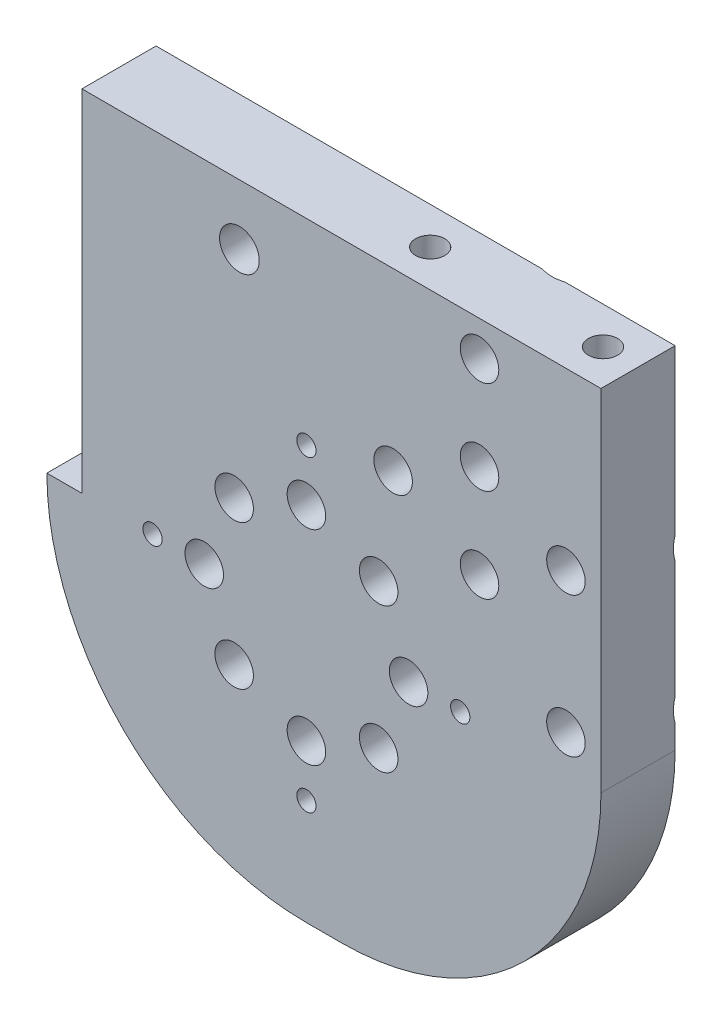
SolidWorks part; units mm, degrees
ref_plane "Front Plane" through (0, 0, 0) normal (0, 0, 1) x (1, 0, 0)
ref_plane "Top Plane" through (0, 0, 0) normal (0, 1, 0) x (1, 0, 0)
ref_plane "Right Plane" through (0, 0, 0) normal (1, 0, 0) x (0, 0, -1)
ref_plane "Plane1" through (0, 0, 0) normal (0, 0, -1) x (-1, 0, 0)
sketch "Sketch1" plane through (0, 0, 0) normal (0, 0, -1) x (-1, 0, 0)
  line L0 (44.45, 0) -> (44.45, 60)
  line L1 (44.45, 60) -> (-44.45, 60)
  line L2 (-44.45, 60) -> (-44.45, 0)
  arc A0 (-44.45, 0) -> (44.45, 0) centre (0, 0) ccw
extrude "Boss-Extrude1" add sketch "Sketch1" against normal blind 12.7
hole_wizard "#4 Clearance Hole1" positions "Sketch3" profile "Sketch2" hole size "#4" standard "ANSI Inch"
sketch "Sketch3" plane through (0, 0, 12.7) normal (0, 0, 1) x (1, 0, 0)
  line L0 (6, 0) -> (6, 26.35) construction
  line L1 (6, 0) -> (32.35, 0) construction
  line L2 (6, 0) -> (6, -26.35) construction
  line L3 (6, 0) -> (-20.35, 0) construction
  circle A0 centre (6, 0) radius 26.35 construction
  point P0 (32.35, 0.009)
  point P1 (6, -26.35)
  point P2 (-20.35, -0.01)
  point P3 (6, 26.35)
  dimension "D1" = 52.7
  dimension "D2" = 6
sketch "Sketch2" plane through (32.35, 0.009, 12.7) normal (1, 0, 0) x (0, -1, 0)
  line L0 (0, 0) -> (0, 12.7)
  line L1 (0, 12.7) -> (1.65, 12.7)
  line L2 (1.65, 12.7) -> (1.65, 0)
  line L5 (1.65, 0) -> (0, 0)
  line L11 (0, -6.35) -> (0, 107.95) construction
  dimension "Thru Hole Dia." = 3.3
  dimension "Thru Hole Depth" = 12.7
hole_wizard "1/4 Clearance Hole1" positions "Sketch5" profile "Sketch4" hole size "1/4" standard "ANSI Inch"
sketch "Sketch5" plane through (0, 0, 0) normal (0, 0, -1) x (-1, 0, 0)
  point P0 (8.85, 30)
  point P1 (23.65, 38)
  point P2 (23.65, 22)
sketch "Sketch4" plane through (-8.85, 30, 0) normal (1, 0, 0) x (0, 1, 0)
  line L0 (0, 0) -> (0, 12.7)
  line L1 (0, 12.7) -> (3.3, 12.7)
  line L2 (3.3, 12.7) -> (3.3, 0)
  line L5 (3.3, 0) -> (0, 0)
  line L11 (0, -6.35) -> (0, 107.95) construction
  dimension "Thru Hole Dia." = 6.6
  dimension "Thru Hole Depth" = 12.7
hole_wizard "1/4 Clearance Hole2" positions "Sketch7" profile "Sketch6" hole size "1/4" standard "ANSI Inch"
sketch "Sketch7" plane through (0, 0, 12.7) normal (0, 0, 1) x (1, 0, 0)
  line L0 (0, 0) -> (0, 60) construction
  line L1 (-44.45, 60) -> (44.45, 60) construction
  point P0 (17.4725, 49.6929)
  dimension "D1" = 17.4725
sketch "Sketch6" plane through (17.4725, 49.6929, 12.7) normal (1, 0, 0) x (0, -1, 0)
  line L0 (0, 0) -> (0, 12.7)
  line L1 (0, 12.7) -> (3.4, 12.7)
  line L2 (3.4, 12.7) -> (3.4, 0)
  line L5 (3.4, 0) -> (0, 0)
  line L11 (0, -6.35) -> (0, 107.95) construction
  dimension "Thru Hole Dia." = 6.8
  dimension "Thru Hole Depth" = 12.7
hole_wizard "CSK for 1/4 Flat Head Machine Screw (100)1" positions "Sketch9" profile "Sketch8" countersink size "1/4" standard "ANSI Inch"
sketch "Sketch9" plane through (0, 0, 0) normal (0, 0, -1) x (-1, 0, 0)
  point P0 (23.65, 54)
  point P1 (38.45, 6)
  point P2 (38.45, 30)
sketch "Sketch8" plane through (-23.65, 54, 0) normal (1, 0, 0) x (0, 1, 0)
  line L0 (0, 0) -> (0, 12.7)
  line L1 (0, 12.7) -> (3.3, 12.7)
  line L2 (3.3, 12.7) -> (3.3, 3)
  line L3 (3.3, 3) -> (6.3, 0)
  line L5 (6.3, 0) -> (0, 0)
  line L6 (-3.3, 3) -> (-6.3, 0) construction
  line L11 (0, -6.35) -> (0, 107.95) construction
  dimension "Thru Hole Dia." = 6.6
  dimension "Thru Hole Depth" = 12.7
  dimension "Near C'Sink Dia." = 12.6
  dimension "Near C'Sink Angle" = 90
hole_wizard "#10 Clearance Hole1" positions "Sketch11" profile "Sketch10" hole size "#10" standard "ANSI Inch"
sketch "Sketch11" plane through (0, 60, 0) normal (0, 1, 0) x (1, 0, 0)
  point P0 (-38.45, -6.35)
  point P1 (-8.85, -6.35)
sketch "Sketch10" plane through (-38.45, 60, 6.35) normal (1, 0, 0) x (0, 0, 1)
  line L0 (0, 0) -> (0, 15)
  line L1 (0, 15) -> (2.5, 15)
  line L2 (2.5, 15) -> (2.5, 0)
  line L5 (2.5, 0) -> (0, 0)
  line L10 (0, 15) -> (-2.5, 15) construction
  line L11 (0, -6.35) -> (0, 107.95) construction
  dimension "Hole Dia." = 5
  dimension "Hole Depth" = 15
  dimension "Drill Angle" = 180
hole_wizard "#10 Clearance Hole2" positions "Sketch13" profile "Sketch12" hole size "#10" standard "ANSI Inch"
sketch "Sketch13" plane through (44.45, 0, 0) normal (1, 0, 0) x (0, 0, -1)
  point P0 (-6.35, 7)
  point P1 (-6.35, 53)
  point P2 (-6.35, 30)
sketch "Sketch12" plane through (44.45, 7, 6.35) normal (0, 1, 0) x (0, 0, -1)
  line L0 (0, 0) -> (0, 10)
  line L1 (0, 10) -> (2.5, 10)
  line L2 (2.5, 10) -> (2.5, 0)
  line L5 (2.5, 0) -> (0, 0)
  line L10 (0, 10) -> (-2.5, 10) construction
  line L11 (0, -6.35) -> (0, 107.95) construction
  dimension "Hole Dia." = 5
  dimension "Hole Depth" = 10
  dimension "Drill Angle" = 180
hole_wizard "1-3/4 Clearance Hole1" positions "Sketch15" profile "Sketch14" hole size "1-3/4" standard "ANSI Inch"
sketch "Sketch15" plane through (0, 0, 0) normal (0, 0, -1) x (-1, 0, 0)
  point P0 (-6, 0)
  dimension "D1" = 6
sketch "Sketch14" plane through (6, 0, 0) normal (1, 0, 0) x (0, 1, 0)
  line L0 (0, 0) -> (0, 5)
  line L1 (0, 5) -> (22.5, 5)
  line L2 (22.5, 5) -> (22.5, 0)
  line L5 (22.5, 0) -> (0, 0)
  line L10 (0, 5) -> (-22.5, 5) construction
  line L11 (0, -6.35) -> (0, 107.95) construction
  dimension "Hole Dia." = 45
  dimension "Hole Depth" = 5
  dimension "Drill Angle" = 180
hole_wizard "1/4 Clearance Hole3" positions "Sketch17" profile "Sketch16" hole size "1/4" standard "ANSI Inch"
sketch "Sketch17" plane through (0, 0, 12.7) normal (0, 0, 1) x (1, 0, 0)
  line L0 (6, 0) -> (6, 17.5) construction
  line L2 (6, 0) -> (-6.3744, 12.3744) construction
  line L4 (6, 0) -> (-11.5, 0) construction
  line L5 (6, 0) -> (-6.3744, -12.3744) construction
  line L6 (6, 0) -> (6, -17.5) construction
  line L7 (6, 0) -> (18.3744, -12.3744) construction
  line L8 (6, 0) -> (23.5, 0) construction
  line L9 (6, 0) -> (18.3744, 12.3744) construction
  circle A0 centre (6, 0) radius 17.5 construction
  point P0 (18.3744, 12.3744)
  point P1 (23.5, -0.0012)
  point P2 (18.3744, -12.3744)
  point P3 (6, -17.5)
  point P4 (-6.3744, -12.3744)
  point P5 (-11.5, 0)
  point P6 (-6.3744, 12.3744)
  point P7 (6, 17.5)
  dimension "D1" = 35
  dimension "D2" = 45
  dimension "D3" = 45
  dimension "D4" = 45
  dimension "D5" = 45
  dimension "D6" = 6
sketch "Sketch16" plane through (18.3744, 12.3744, 12.7) normal (1, 0, 0) x (0, -1, 0)
  line L0 (0, 0) -> (0, 12.7)
  line L1 (0, 12.7) -> (3.3, 12.7)
  line L2 (3.3, 12.7) -> (3.3, 0)
  line L5 (3.3, 0) -> (0, 0)
  line L11 (0, -6.35) -> (0, 107.95) construction
  dimension "Thru Hole Dia." = 6.6
  dimension "Thru Hole Depth" = 12.7
chamfer "Chamfer1" distance 3 angle 45 3 edges at (-26.95, 38, 0) (-12.15, 30, 0) (-26.95, 22, 0)
sketch "Sketch18" plane through (0, 0, 0) normal (0, 0, -1) x (-1, 0, 0)
  line L0 (44.45, 0) -> (-44.45, 0) construction
  line L1 (-44.45, 0) -> (-50.45, 0)
  line L2 (-6, -44.45) -> (0, -44.45)
  arc A0 (-50.45, 0) -> (-6, -44.45) centre (-6, 0) ccw
  arc A1 (-44.45, 0) -> (44.45, 0) centre (0, 0) ccw construction
  arc A2 (-44.45, 0) -> (0, -44.45) centre (0, 0) ccw
  dimension "D1" = 88.9
extrude "Boss-Extrude2" add sketch "Sketch18" against normal up to surface (12.7 mm away) up to face at (21.6744, 12.3744, 12.7)
mirror "镜向1" about plane through (-44.45, 0, 12.7) normal (-1, 0, 0) of bodies 112
sketch "草图1" plane through (0, 0, 0) normal (0, 0, -1) x (-1, 0, 0)
  line L1 (44.45, 70.2036) -> (-82.4243, 70.2036)
  line L2 (44.45, 70.2036) -> (44.45, -60.0997)
  line L3 (44.45, -60.0997) -> (-82.4243, -60.0997)
  line L4 (-82.4243, 70.2036) -> (-82.4243, -60.0997)
extrude "切除-拉伸1" cut sketch "草图1" against normal through all
mirror "镜向3" about plane through (-44.45, 70.2036, 12.7) normal (-1, 0, 0) of bodies 114
sketch "草图4" plane through (0, 0, 12.7) normal (0, 0, 1) x (1, 0, 0)
  line L1 (-44.45, 69.0129) -> (-164.3152, 69.0129)
  line L2 (-44.45, 69.0129) -> (-44.45, -67.0541)
  line L3 (-44.45, -67.0541) -> (-164.3152, -67.0541)
  line L4 (-164.3152, 69.0129) -> (-164.3152, -67.0541)
extrude "切除-拉伸3" cut sketch "草图4" against normal through all
mirror "镜向4" about plane through (-44.45, 69.0129, -0.3765) normal (1, 0, 0) of bodies 118
sketch "草图5" plane through (0, 0, 12.7) normal (0, 0, 1) x (1, 0, 0)
  line L1 (-44.45, 68.1866) -> (60.4382, 68.1866)
  line L2 (-44.45, 68.1866) -> (-44.45, -52.8383)
  line L3 (-44.45, -52.8383) -> (60.4382, -52.8383)
  line L4 (60.4382, 68.1866) -> (60.4382, -52.8383)
extrude "切除-拉伸4" cut sketch "草图5" against normal through all
